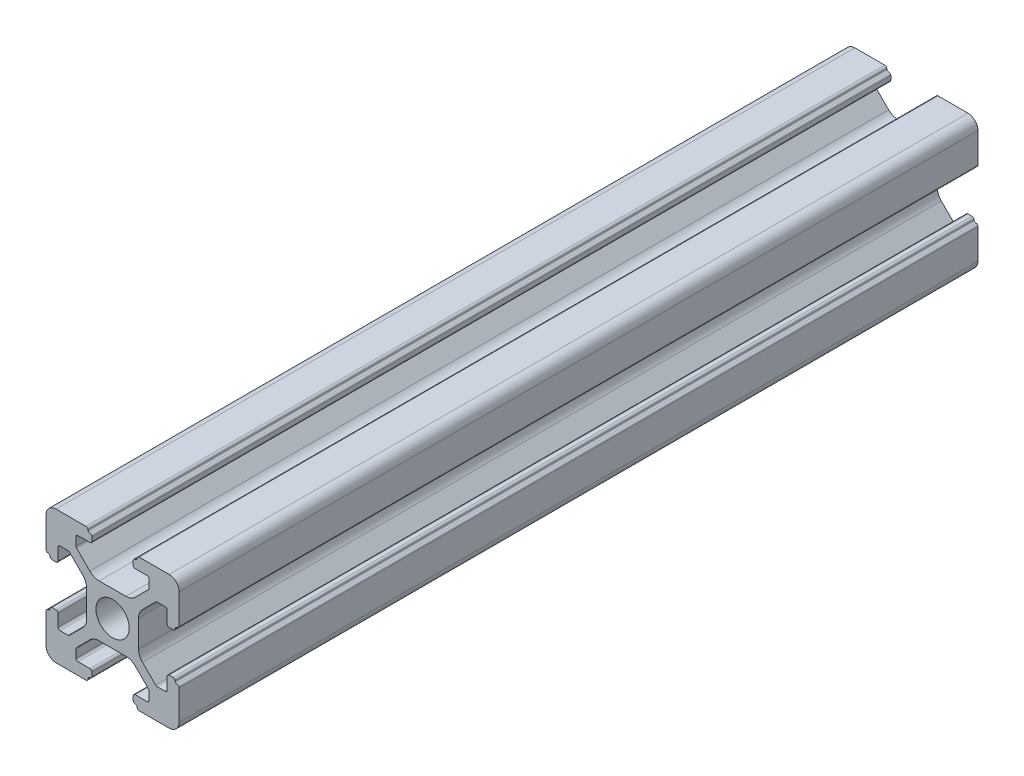
SolidWorks part; units mm, degrees
material "1060 合金"
ref_plane "前视基准面" through (0, 0, 0) normal (0, 0, 1) x (1, 0, 0)
ref_plane "上视基准面" through (0, 0, 0) normal (0, 1, 0) x (1, 0, 0)
ref_plane "右视基准面" through (0, 0, 0) normal (1, 0, 0) x (0, 0, -1)
other "Configuration Table"
sketch "草图1" plane through (0, 0, 0) normal (0, 0, 1) x (1, 0, 0)
  line L0 (24.3588, 8.5519) -> (29.3588, 8.5519) construction
  line L1 (36.8588, 17.0519) -> (36.8588, 12.5519)
  line L2 (26.8588, 11.0519) -> (26.8588, 6.0519) construction
  line L3 (36.8588, 0.0519) -> (36.8588, 4.5519)
  line L4 (35.9588, 5.4519) -> (35.3588, 5.4519)
  line L5 (35.9588, 11.6519) -> (35.3588, 11.6519)
  line L6 (35.0588, 11.9519) -> (35.0588, 13.7519)
  line L7 (34.7588, 14.0519) -> (33.5437, 14.0519)
  line L8 (33.3316, 13.9641) -> (31.3446, 11.9771)
  line L9 (30.7588, 10.5628) -> (30.7588, 6.541)
  line L10 (26.8588, 8.5519) -> (36.8588, 18.5519) construction
  line L11 (35.0588, 5.1519) -> (35.0588, 3.3519)
  line L12 (34.7588, 3.0519) -> (33.5437, 3.0519)
  line L13 (33.3316, 3.1398) -> (31.3446, 5.1268)
  line L14 (32.2709, 15.0247) -> (30.2839, 13.0377)
  line L15 (32.3588, 16.4519) -> (32.3588, 15.2369)
  line L16 (30.2588, 16.7519) -> (32.0588, 16.7519)
  line L17 (29.9588, 17.6519) -> (29.9588, 17.0519)
  line L18 (35.3588, 18.5519) -> (30.8588, 18.5519)
  line L19 (21.4466, 15.0247) -> (23.4336, 13.0377)
  line L20 (21.3588, 16.4519) -> (21.3588, 15.2369)
  line L21 (23.4588, 16.7519) -> (21.6588, 16.7519)
  line L22 (28.8697, 12.4519) -> (24.8479, 12.4519)
  line L23 (23.7588, 17.6519) -> (23.7588, 17.0519)
  line L24 (18.3588, 18.5519) -> (22.8588, 18.5519)
  line L25 (16.8588, 18.5519) -> (26.8588, 8.5519) construction
  line L26 (16.8588, 17.0519) -> (16.8588, 12.5519)
  line L27 (17.7588, 11.6519) -> (18.3588, 11.6519)
  line L28 (22.9588, 6.541) -> (22.9588, 10.5628)
  line L29 (18.6588, 11.9519) -> (18.6588, 13.7519)
  line L30 (18.9588, 14.0519) -> (20.1738, 14.0519)
  line L31 (20.386, 13.9641) -> (22.373, 11.9771)
  line L32 (16.8588, 0.0519) -> (16.8588, 4.5519)
  line L33 (17.7588, 5.4519) -> (18.3588, 5.4519)
  line L34 (18.6588, 5.1519) -> (18.6588, 3.3519)
  line L35 (18.9588, 3.0519) -> (20.1738, 3.0519)
  line L36 (20.386, 3.1398) -> (22.373, 5.1268)
  line L37 (32.2709, 2.0791) -> (30.2839, 4.0661)
  line L38 (32.3588, 0.6519) -> (32.3588, 1.867)
  line L39 (30.2588, 0.3519) -> (32.0588, 0.3519)
  line L40 (24.8479, 4.6519) -> (28.8697, 4.6519)
  line L41 (21.4466, 2.0791) -> (23.4336, 4.0661)
  line L42 (21.3588, 0.6519) -> (21.3588, 1.867)
  line L43 (23.4588, 0.3519) -> (21.6588, 0.3519)
  line L44 (23.7588, -0.5481) -> (23.7588, 0.0519)
  line L45 (29.9588, -0.5481) -> (29.9588, 0.0519)
  line L46 (35.3588, -1.4481) -> (30.8588, -1.4481)
  line L47 (18.3588, -1.4481) -> (22.8588, -1.4481)
  circle A0 centre (26.8588, 8.5519) radius 2.5
  arc A1 (31.3446, 11.9771) -> (30.7588, 10.5628) centre (32.7588, 10.5628) ccw
  arc A2 (36.8588, 12.5519) -> (36.5588, 12.2519) centre (36.5588, 12.5519) cw
  arc A3 (35.9588, 11.6519) -> (36.2588, 11.9519) centre (35.9588, 11.9519) ccw
  arc A4 (35.3588, 11.6519) -> (35.0588, 11.9519) centre (35.3588, 11.9519) cw
  arc A5 (35.0588, 13.7519) -> (34.7588, 14.0519) centre (34.7588, 13.7519) ccw
  arc A6 (33.5437, 14.0519) -> (33.3316, 13.9641) centre (33.5437, 13.7519) ccw
  arc A7 (36.2588, 11.9519) -> (36.5588, 12.2519) centre (36.5588, 11.9519) cw
  arc A8 (36.8588, 4.5519) -> (36.5588, 4.8519) centre (36.5588, 4.5519) ccw
  arc A9 (36.2588, 5.1519) -> (36.5588, 4.8519) centre (36.5588, 5.1519) ccw
  arc A10 (35.9588, 5.4519) -> (36.2588, 5.1519) centre (35.9588, 5.1519) cw
  arc A11 (35.3588, 5.4519) -> (35.0588, 5.1519) centre (35.3588, 5.1519) ccw
  arc A12 (35.0588, 3.3519) -> (34.7588, 3.0519) centre (34.7588, 3.3519) cw
  arc A13 (33.5437, 3.0519) -> (33.3316, 3.1398) centre (33.5437, 3.3519) cw
  arc A14 (31.3446, 5.1268) -> (30.7588, 6.541) centre (32.7588, 6.541) cw
  arc A15 (30.2588, 17.9519) -> (30.5588, 18.2519) centre (30.2588, 18.2519) ccw
  arc A16 (32.3588, 15.2369) -> (32.2709, 15.0247) centre (32.0588, 15.2369) cw
  arc A17 (32.0588, 16.7519) -> (32.3588, 16.4519) centre (32.0588, 16.4519) cw
  arc A18 (29.9588, 17.0519) -> (30.2588, 16.7519) centre (30.2588, 17.0519) ccw
  arc A19 (29.9588, 17.6519) -> (30.2588, 17.9519) centre (30.2588, 17.6519) cw
  arc A20 (30.8588, 18.5519) -> (30.5588, 18.2519) centre (30.8588, 18.2519) ccw
  arc A21 (23.4336, 13.0377) -> (24.8479, 12.4519) centre (24.8479, 14.4519) ccw
  arc A22 (21.3588, 15.2369) -> (21.4466, 15.0247) centre (21.6588, 15.2369) ccw
  arc A23 (21.6588, 16.7519) -> (21.3588, 16.4519) centre (21.6588, 16.4519) ccw
  arc A24 (23.7588, 17.0519) -> (23.4588, 16.7519) centre (23.4588, 17.0519) cw
  arc A25 (23.7588, 17.6519) -> (23.4588, 17.9519) centre (23.4588, 17.6519) ccw
  arc A26 (23.4588, 17.9519) -> (23.1588, 18.2519) centre (23.4588, 18.2519) cw
  arc A27 (22.8588, 18.5519) -> (23.1588, 18.2519) centre (22.8588, 18.2519) cw
  arc A28 (30.2839, 13.0377) -> (28.8697, 12.4519) centre (28.8697, 14.4519) cw
  arc A29 (22.373, 5.1268) -> (22.9588, 6.541) centre (20.9588, 6.541) ccw
  arc A30 (16.8588, 12.5519) -> (17.1588, 12.2519) centre (17.1588, 12.5519) ccw
  arc A31 (17.4588, 11.9519) -> (17.1588, 12.2519) centre (17.1588, 11.9519) ccw
  arc A32 (17.7588, 11.6519) -> (17.4588, 11.9519) centre (17.7588, 11.9519) cw
  arc A33 (18.3588, 11.6519) -> (18.6588, 11.9519) centre (18.3588, 11.9519) ccw
  arc A34 (18.6588, 13.7519) -> (18.9588, 14.0519) centre (18.9588, 13.7519) cw
  arc A35 (20.1738, 14.0519) -> (20.386, 13.9641) centre (20.1738, 13.7519) cw
  arc A36 (22.373, 11.9771) -> (22.9588, 10.5628) centre (20.9588, 10.5628) cw
  arc A37 (16.8588, 4.5519) -> (17.1588, 4.8519) centre (17.1588, 4.5519) cw
  arc A38 (17.7588, 5.4519) -> (17.4588, 5.1519) centre (17.7588, 5.1519) ccw
  arc A39 (18.3588, 5.4519) -> (18.6588, 5.1519) centre (18.3588, 5.1519) cw
  arc A40 (18.6588, 3.3519) -> (18.9588, 3.0519) centre (18.9588, 3.3519) ccw
  arc A41 (20.1738, 3.0519) -> (20.386, 3.1398) centre (20.1738, 3.3519) ccw
  arc A42 (17.4588, 5.1519) -> (17.1588, 4.8519) centre (17.1588, 5.1519) cw
  arc A43 (30.2839, 4.0661) -> (28.8697, 4.6519) centre (28.8697, 2.6519) ccw
  arc A44 (32.3588, 1.867) -> (32.2709, 2.0791) centre (32.0588, 1.867) ccw
  arc A45 (32.0588, 0.3519) -> (32.3588, 0.6519) centre (32.0588, 0.6519) ccw
  arc A46 (29.9588, 0.0519) -> (30.2588, 0.3519) centre (30.2588, 0.0519) cw
  arc A47 (29.9588, -0.5481) -> (30.2588, -0.8481) centre (30.2588, -0.5481) ccw
  arc A48 (30.2588, -0.8481) -> (30.5588, -1.1481) centre (30.2588, -1.1481) cw
  arc A49 (30.8588, -1.4481) -> (30.5588, -1.1481) centre (30.8588, -1.1481) cw
  arc A50 (23.4588, -0.8481) -> (23.1588, -1.1481) centre (23.4588, -1.1481) ccw
  arc A51 (21.3588, 1.867) -> (21.4466, 2.0791) centre (21.6588, 1.867) cw
  arc A52 (21.6588, 0.3519) -> (21.3588, 0.6519) centre (21.6588, 0.6519) cw
  arc A53 (23.7588, 0.0519) -> (23.4588, 0.3519) centre (23.4588, 0.0519) ccw
  arc A54 (23.7588, -0.5481) -> (23.4588, -0.8481) centre (23.4588, -0.5481) cw
  arc A55 (22.8588, -1.4481) -> (23.1588, -1.1481) centre (22.8588, -1.1481) ccw
  arc A56 (23.4336, 4.0661) -> (24.8479, 4.6519) centre (24.8479, 2.6519) cw
  arc A57 (16.8588, 0.0519) -> (18.3588, -1.4481) centre (18.3588, 0.0519) ccw
  arc A58 (35.3588, -1.4481) -> (36.8588, 0.0519) centre (35.3588, 0.0519) ccw
  arc A59 (36.8588, 17.0519) -> (35.3588, 18.5519) centre (35.3588, 17.0519) ccw
  arc A60 (16.8588, 17.0519) -> (18.3588, 18.5519) centre (18.3588, 17.0519) cw
  point P47 (30.7588, 8.5519)
  point P86 (26.8588, 12.4519)
  point P164 (22.9588, 8.5519)
  point P165 (26.8588, 4.6519)
  dimension "D1" = 5
extrude "凸台-拉伸1" add sketch "草图1" along normal blind 120
